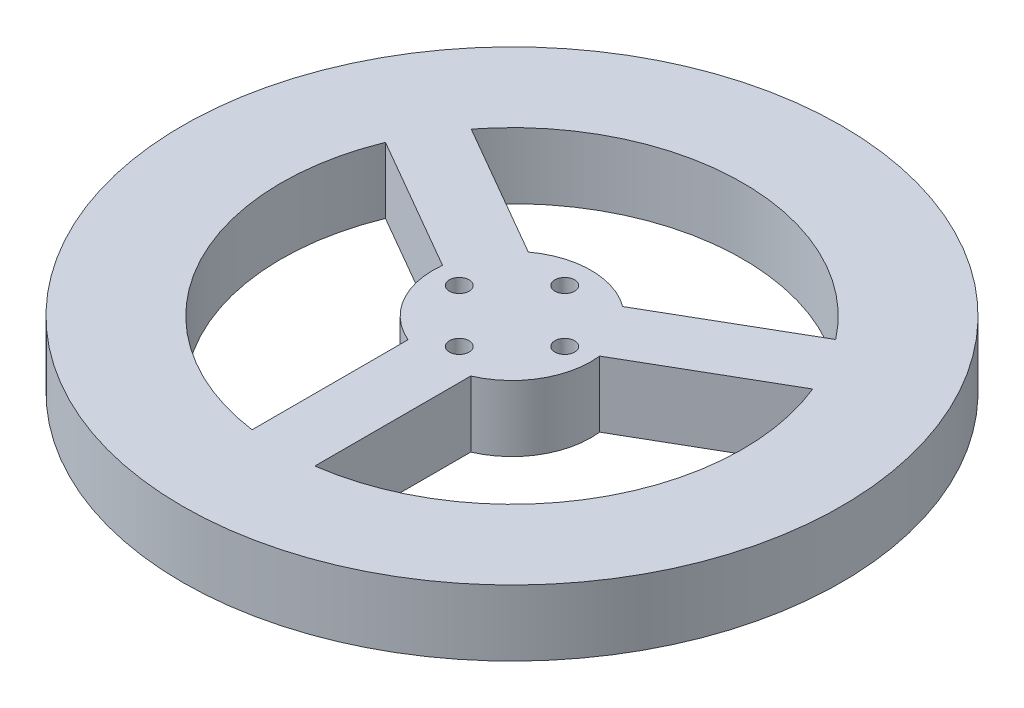
SolidWorks part; units mm, degrees
material "AISI 1020"
ref_plane "Front Plane" through (0, 0, 0) normal (0, 0, 1) x (1, 0, 0)
ref_plane "Top Plane" through (0, 0, 0) normal (0, 1, 0) x (1, 0, 0)
ref_plane "Right Plane" through (0, 0, 0) normal (1, 0, 0) x (0, 0, -1)
sketch "Sketch2" plane through (0, 0, 0) normal (0, 1, 0) x (1, 0, 0)
  line L0 (0, 5.5) -> (-27.6473, 21.4622)
  line L1 (0, 5.5) -> (27.6473, 21.4622)
  line L2 (4.7631, -2.75) -> (32.4105, 13.2122)
  line L3 (4.7631, -2.75) -> (4.7631, -34.6744)
  line L4 (-4.7631, -2.75) -> (-4.7631, -34.6744)
  line L5 (-4.7631, -2.75) -> (-32.4105, 13.2122)
  circle A0 centre (0, 0) radius 50
  circle A1 centre (0, 0) radius 12
  circle A2 centre (0, 0) radius 35
  circle A3 centre (0, 0) radius 5.5
  point P8 (0, 0)
  point P13 (0, 0)
  point P19 (0, 0)
  dimension "D1" = 100
  dimension "D4" = 24
  dimension "D5" = 70
  dimension "D3" = 11
  dimension "D2" = 120
extrude "Boss-Extrude1" add sketch "Sketch2" along normal blind 10 contours A0 A2 | A3 L0 A1 L5 | L1 A1 L0 | A3 L2 A1 L1 | L3 A1 L2 | A3 L4 A1 L3 | L5 A1 L4 | A3 | L4 A2 L3 A1 | L0 A2 L5 A1 | L2 A2 L1 A1
sketch "Sketch3" plane through (0, 10, 0) normal (0, 1, 0) x (1, 0, 0)
  circle A0 centre (0, 0) radius 8 construction
  circle A1 centre (0, 8) radius 1.5
  circle A2 centre (8, 0) radius 1.5
  circle A3 centre (0, -8) radius 1.5
  circle A4 centre (-8, 0) radius 1.5
  point P14 (0, 0)
  dimension "D1" = 16
  dimension "D2" = 3
extrude "Cut-Extrude1" cut sketch "Sketch3" against normal blind 5
